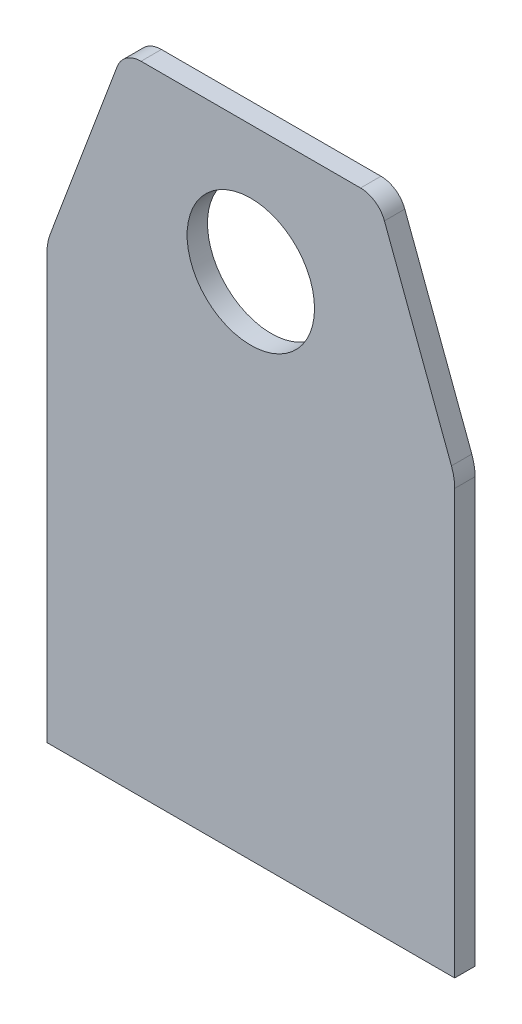
SolidWorks part; units mm, degrees
ref_plane "Front Plane" through (0, 0, 0) normal (0, 0, 1) x (1, 0, 0)
ref_plane "Top Plane" through (0, 0, 0) normal (0, 1, 0) x (1, 0, 0)
ref_plane "Right Plane" through (0, 0, 0) normal (1, 0, 0) x (0, 0, -1)
sketch "Sketch2" plane through (0, 0, 0) normal (0, 0, 1) x (1, 0, 0)
  line L0 (-80, 0) -> (-80, 170)
  line L1 (88, 0) -> (-88, 0) construction
  line L2 (-80, 170) -> (-50, 250)
  line L3 (-50, 250) -> (50, 250)
  line L4 (0, -137.5) -> (0, 137.5) construction
  line L6 (80, 0) -> (-80, 0)
  line L7 (80, 170) -> (50, 250)
  line L8 (80, 0) -> (80, 170)
  dimension "D1" = 170
extrude "Boss-Extrude1" add sketch "Sketch2" along normal blind 8
sketch "Sketch4" plane through (0, 0, 8) normal (0, 0, 1) x (1, 0, 0)
  line L0 (0, 175) -> (0, 200) construction
  line L1 (0, -4.4) -> (0, 4.4) construction
  circle A0 centre (0, 200) radius 25
  dimension "D2" = 50
extrude "Cut-Extrude1" cut sketch "Sketch4" against normal blind 8
fillet "Fillet2" radius 20 1 edges at (-80, 170, 4)
fillet "Fillet4" radius 20 1 edges at (80, 170, 4)
fillet "Fillet5" radius 10 2 edges at (-50, 250, 4) (50, 250, 4)
